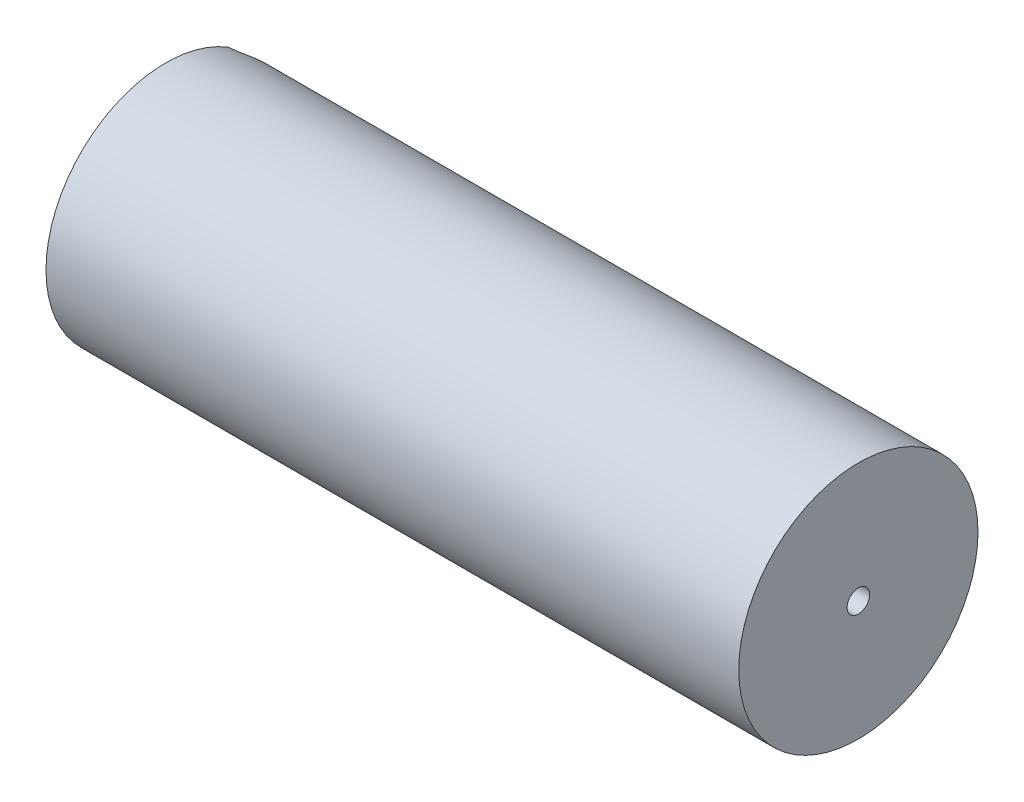
SolidWorks part; units mm, degrees
ref_plane "前视基准面" through (0, 0, 0) normal (0, 0, 1) x (1, 0, 0)
ref_plane "上视基准面" through (0, 0, 0) normal (0, 1, 0) x (1, 0, 0)
ref_plane "右视基准面" through (0, 0, 0) normal (1, 0, 0) x (0, 0, -1)
sketch "草图1" plane through (0, 0, 0) normal (0, 0, 1) x (1, 0, 0)
  line L0 (0, 0) -> (153.4736, 0) construction
  line L1 (0, 2.5) -> (153.4736, 2.5)
  line L2 (153.4736, 2.5) -> (153.4736, 26.5)
  line L3 (153.4736, 26.5) -> (0, 26.5)
  line L4 (0, 26.5) -> (0, 2.5)
revolve "旋转1" add sketch "草图1" angle 360 about L0
sketch "草图2" plane through (0, 0, 0) normal (0, 0, 1) x (1, 0, 0)
  line L0 (0, 26.5) -> (0, -26.5) construction
  circle A0 centre (0, 19) radius 3.5
extrude "切除-拉伸1" cut sketch "草图2" against normal blind 230.2104
